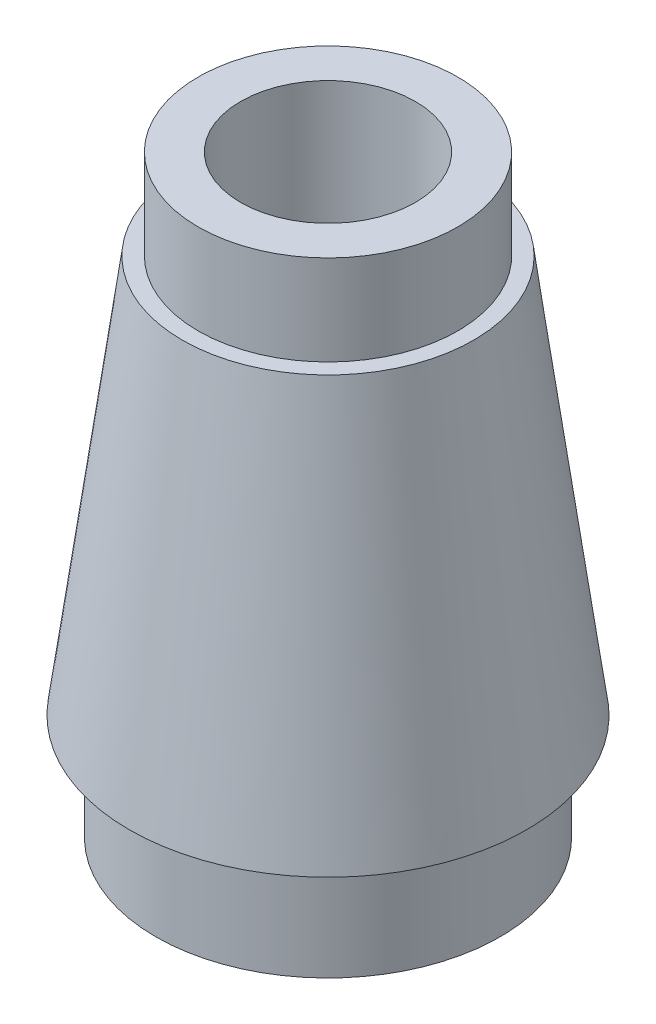
SolidWorks part; units mm, degrees
ref_plane "Front Plane" through (0, 0, 0) normal (0, 0, 1) x (1, 0, 0)
ref_plane "Top Plane" through (0, 0, 0) normal (0, 1, 0) x (1, 0, 0)
ref_plane "Right Plane" through (0, 0, 0) normal (1, 0, 0) x (0, 0, -1)
sketch "Sketch1" plane through (0, 0, 0) normal (0, 1, 0) x (1, 0, 0)
  circle A0 centre (0, 0) radius 3.75
  dimension "D1" = 7.5
ref_plane "Plane1" through (0, 7.5, 0) normal (0, 1, 0) x (1, 0, 0)
sketch "Sketch2" plane through (0, 7.5, 0) normal (0, 1, 0) x (1, 0, 0)
  circle A0 centre (0, 0) radius 2.75
  dimension "D1" = 5.5
loft "Loft1" add profiles "Sketch2", "Sketch1"
sketch "Sketch3" plane through (0, 7.5, 0) normal (0, 1, 0) x (1, 0, 0)
  circle A0 centre (0, 0) radius 2.45
  circle A1 centre (0, 0) radius 1.65
  dimension "D1" = 4.9
  dimension "D2" = 0.8
extrude "Boss-Extrude1" add sketch "Sketch3" along normal blind 1.7
sketch "Sketch4" plane through (0, 0, 0) normal (0, -1, 0) x (1, 0, 0)
  circle A0 centre (0, 0) radius 3.25
  circle A1 centre (0, 0) radius 2.45
  dimension "D1" = 6.5
  dimension "D2" = 0.8
extrude "Boss-Extrude2" add sketch "Sketch4" along normal blind 2
sketch "Sketch5" plane through (0, 7.5, 0) normal (0, 1, 0) x (1, 0, 0)
  circle A1 centre (0, 0) radius 1.65
  circle A2 centre (0, 0) radius 1.65
  dimension "D1" = 0
extrude "Cut-Extrude1" cut sketch "Sketch5" against normal through all
